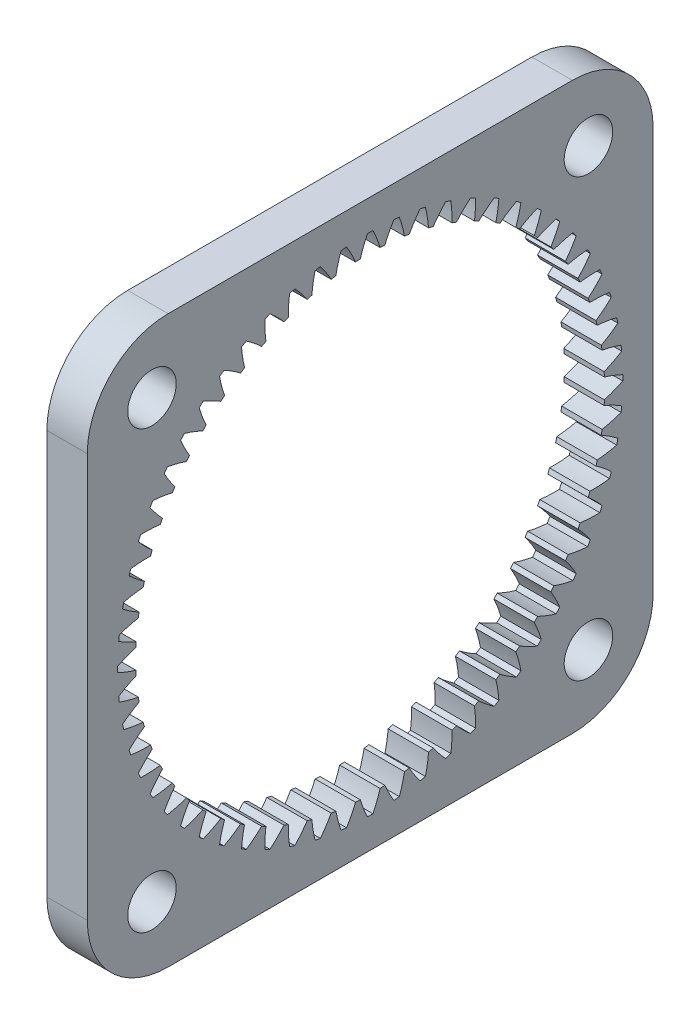
SolidWorks part; units mm, degrees
ref_plane "Plane1" through (0, 0, 0) normal (0, 0, 1) x (1, 0, 0)
ref_plane "Plane2" through (0, 0, 0) normal (0, 1, 0) x (1, 0, 0)
ref_plane "Plane3" through (0, 0, 0) normal (1, 0, 0) x (0, 0, -1)
sketch "HoldingSke" plane through (0, 0, 0) normal (0, 1, 0) x (1, 0, 0)
  line L0 (0, 0) -> (0.5, -0.866)
  line L1 (-15, 0) -> (100, 0) construction
  line L2 (0, 0) -> (-2.1039, 2.3779)
  line L3 (0, 0) -> (-11.863, 4.5341)
  line L4 (0, 0) -> (4.318, 7.479)
  line L5 (0, 0) -> (-23.7986, -8.8762)
  line L6 (0, 0) -> (-10.5278, -7.1032)
  line L7 (-2.1039, 2.3779) -> (3.3635, 27.1825)
  line L8 (-76.2, 3.3779) -> (-54.61, 3.3779)
  line L9 (-71.009, 38.7566) -> (-53.1078, 45.2721)
  line L10 (-76.2, 71.12) -> (104.1128, 71.12)
  line L11 (0, 0) -> (-5, 0)
  line L12 (-76.2, 101.6) -> (-76.162, 101.6)
  line L13 (24.9733, 27.94) -> (52.9518, 28.4284)
  line L14 (24.9733, 27.94) -> (24.9743, 27.94)
  line L15 (24.9733, 27.94) -> (100.4006, 29.5858)
  circle A0 centre (0, 0) radius 35
  circle A1 centre (0, 0) radius 12.7
  circle A2 centre (0, 0) radius 12.7
  dimension "MHD" = 25.4
  dimension "Hub_dia" = 25.4
  dimension "Diameter" = 70
  dimension "Num_teeth" = 60
  dimension "Pitch" = 1
  dimension "Overall_len" = 25.4
  dimension "Show_teeth" = 60
  dimension "Thickness" = 12.7
  dimension "OAL" = 25.4001
  dimension "T_dim" = 21.59
  dimension "Ap" = 20
  dimension "H" = 19.05
  dimension "Pitch_radius" = 180.3128
  dimension "Width" = 5
  dimension "Backlash" = 0.038
  dimension "Addendum_fac" = 1
  dimension "Dedendum_fac" = 1.25
  dimension "Clearance_fac" = 0.25
  dimension "Dedendum_add" = 0.001
  dimension "Module" = 1
sketch "BasProSke" plane through (0, 0, 0) normal (0, 1, 0) x (1, 0, 0)
  line L0 (-10, 0) -> (60, 0) construction
  line L1 (0, 29) -> (0, 35)
  line L2 (0, 29) -> (5, 29)
  line L3 (5, 29) -> (5, 35)
  line L4 (5, 35) -> (0, 35)
  dimension "Diameter" = 70
  dimension "Thickness" = 5
  dimension "Inside_diameter" = 58
revolve "Base-Revolve" add sketch "BasProSke" angle 360 about L0
sketch "TooCutSke" plane through (0, 0, 0) normal (1, 0, 0) x (0, 0, -1)
  line L3 (0.8803, 29.9871) -> (0.8803, 53.6633) construction
  line L4 (0, 0) -> (0, 59.563) construction
  line L5 (0, 0) -> (-3.576, 68.2339) construction
  line L6 (-13.1633, 24.7167) -> (36.4631, 27.3175) construction
  circle A0 centre (0, 0) radius 30 construction
  circle A1 centre (0, 0) radius 31.251 construction
  circle A2 centre (0, 0) radius 25.3717 construction
  circle A3 centre (0, 0) radius 28.9746 construction
  arc A4 (1.2274, 28.9486) -> (0.3395, 31.2492) centre (-13.1633, 24.7167) ccw
  arc A5 (1.2274, 28.9486) -> (-1.2274, 28.9486) centre (0, 0) ccw
  arc A6 (0.3395, 31.2492) -> (-0.3395, 31.2492) centre (0, 0) ccw
  arc A7 (-0.3395, 31.2492) -> (-1.2274, 28.9486) centre (13.1633, 24.7167) ccw
  dimension "Pitch_dia" = 60
  dimension "Base_dia" = 50.7434
  dimension "Root_dia" = 62.502
  dimension "Overcut_dia" = 57.9492
  dimension "Flank_rad" = 15
  dimension "Half_ang" = 3
  dimension "Half_CT" = 0.8803
extrude "ToothCut" cut sketch "TooCutSke" along normal through all
fillet "Breaks" [suppressed] radius 0.1
fillet "RootFillets" [suppressed] radius 0.251
pattern_circular "TeethCuts" count 60 every 6 about axis through (-10, 0, 0) along (1, 0, 0) of "RootFillets", "Breaks", "ToothCut"
sketch "Croquis2" plane through (0, 0, 0) normal (-1, 0, 0) x (0, 0, 1)
  line L1 (-35, 35) -> (35, 35)
  line L2 (-35, 35) -> (-35, -35)
  line L3 (-35, -35) -> (35, -35)
  line L4 (35, 35) -> (35, -35)
  line L5 (-35, 35) -> (35, -35) construction
  line L6 (-35, -35) -> (35, 35) construction
  circle A0 centre (0, 0) radius 35
  dimension "D1" = 70
  dimension "D2" = 70
extrude "Saliente-Extruir3" add sketch "Croquis2" against normal through all contours A0 L1 L2 | A0 L4 L1 | A0 L3 L4 | A0 L2 L3
fillet "Redondeo1" radius 10 4 edges at (2.5, -35, 35) (2.5, -35, -35) (2.5, 35, 35) (2.5, 35, -35)
sketch "Croquis3" plane through (5, 0, 0) normal (1, 0, 0) x (0, 0, -1)
  line L0 (-35, 25) -> (-35, -25) construction
  line L1 (25, 35) -> (-25, 35) construction
  line L2 (35, 25) -> (35, -25) construction
  line L3 (25, -35) -> (-25, -35) construction
  circle A0 centre (-27, 27) radius 3
  circle A1 centre (27, 27) radius 3
  circle A2 centre (27, -27) radius 3
  circle A3 centre (-27, -27) radius 3
  dimension "D3" = 6
  dimension "D4" = 6
  dimension "D9" = 6
  dimension "D12" = 6
  dimension "D1" = 8
  dimension "D2" = 8
  dimension "D5" = 8
  dimension "D6" = 8
  dimension "D7" = 8
  dimension "D8" = 8
  dimension "D10" = 8
  dimension "D11" = 8
extrude "Cortar-Extruir2" cut sketch "Croquis3" against normal blind 10
sketch "Croquis4" plane through (5, 0, 0) normal (1, 0, 0) x (0, 0, -1)
  circle A0 centre (27, 27) radius 3
equation "' \"Module@HoldingSke\" = 6.35"
equation "' \"Num_teeth@HoldingSke\" = 24"
equation "' \"Ap@HoldingSke\" =  14.5"
equation "' \"Ap@HoldingSke\" = 14.5"
equation "' \"Width@HoldingSke\" = 12"
equation "' \"Diameter@HoldingSke\" = 8 * 25.4"
equation "' \"Show_teeth@HoldingSke\" = 100"
equation "' \"Backlash@HoldingSke\" = 0.009 * 25.4"
equation "' \"Addendum_fac@HoldingSke\" = 1.0"
equation "' \"Dedendum_fac@HoldingSke\" = 1.25"
equation "' \"Dedendum_add@HoldingSke\" = 0.00005 * 25.4"
equation "' \"Clearance_fac@HoldingSke\" = 0.25"
equation "\"Pitch@HoldingSke\" = 1 / \"Module@HoldingSke\" "
equation "\"Overcut_dia@TooCutSke\" = (\"Num_teeth@HoldingSke\" - 2 * \"Addendum_fac@HoldingSke\") / \"Pitch@HoldingSke\" - 0.002 * 25.4"
equation "\"Pitch_dia@TooCutSke\" = \"Num_teeth@HoldingSke\" / \"Pitch@HoldingSke\""
equation "\"Base_dia@TooCutSke\" = \"Num_teeth@HoldingSke\" / \"Pitch@HoldingSke\" * cos((\"Ap@HoldingSke\"  * 3.14159265 / 180)) * 0.90"
equation "\"Root_dia@TooCutSke\" = \"Num_teeth@HoldingSke\"  / \"Pitch@HoldingSke\" + 2 *  \"Dedendum_fac@HoldingSke\"/ \"Pitch@HoldingSke\" + \"Dedendum_add@HoldingSke\" * 2"
equation "\"Half_ang@TooCutSke\" = 180 / \"Num_teeth@HoldingSke\""
equation "\"Half_CT@TooCutSke\" = \"Num_teeth@HoldingSke\" / \"Pitch@HoldingSke\" * sin((3.14159265 / 2 / \"Num_teeth@HoldingSke\")) / 2 + 10 * \"Backlash@HoldingSke\" / 4"
equation "\"Flank_rad@TooCutSke\" = \"Num_teeth@HoldingSke\" / \"Pitch@HoldingSke\" / 4"
equation "\"Radius@RootFillets\"= \"Clearance_fac@HoldingSke\" / \"Pitch@HoldingSke\" + \"Dedendum_add@HoldingSke\""
equation "\"Break_rad@Breaks\" = 0.02 / \"Pitch@HoldingSke\" * 5"
equation "\"Num_teeth@TeethCuts\" = int( \"Show_teeth@HoldingSke\" ) + 1"
equation "\"Num_teeth@TeethCuts\" = ((sgn( \"Num_teeth@TeethCuts\" - \"Num_teeth@HoldingSke\" )-1)*( \"Num_teeth@TeethCuts\" - \"Num_teeth@HoldingSke\" ))/-2+ \"Num_teeth@HoldingSke\""
equation "\"Num_teeth@TeethCuts\" = ((sgn( \"Num_teeth@TeethCuts\" - 2.0)+1)*( \"Num_teeth@TeethCuts\" - 2.0))/2 +2.0"
equation "\"Angle@TeethCuts\" = 360.0 / \"Num_teeth@HoldingSke\""
equation "\"Diameter@BasProSke\" = \"Num_teeth@HoldingSke\"  / \"Pitch@HoldingSke\" + 2 *  \"Dedendum_fac@HoldingSke\"/ \"Pitch@HoldingSke\" + \"Dedendum_add@HoldingSke\" * 2 + 0.002 * 25.4"
equation "\"Diameter@BasProSke\" = ((sgn( \"Diameter@BasProSke\"  - \"Diameter@HoldingSke\" )+1)*( \"Diameter@BasProSke\"  - \"Diameter@HoldingSke\" ))/2 + \"Diameter@HoldingSke\""
equation "\"Inside_diameter@BasProSke\" =  (\"Num_teeth@HoldingSke\" - 2 * \"Addendum_fac@HoldingSke\") / \"Pitch@HoldingSke\" "
equation "\"Thickness@BasProSke\"  = \"Width@HoldingSke\""
